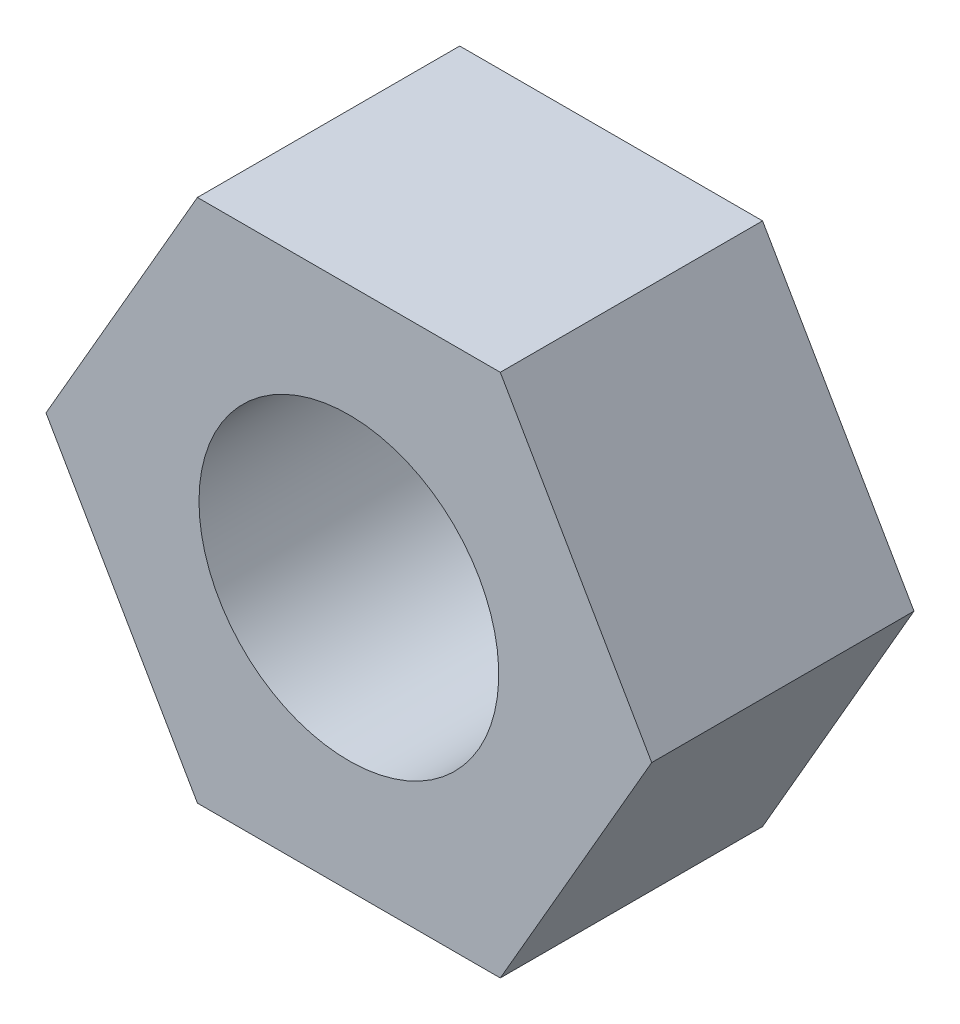
SolidWorks part; units mm, degrees
ref_plane "Front Plane" through (0, 0, 0) normal (0, 0, 1) x (1, 0, 0)
ref_plane "Top Plane" through (0, 0, 0) normal (0, 1, 0) x (1, 0, 0)
ref_plane "Right Plane" through (0, 0, 0) normal (1, 0, 0) x (0, 0, -1)
ref_plane "Plane1" through (0, 0, 177.8) normal (0, 0, 1) x (1, 0, 0)
sketch "Sketch1" plane through (0, 0, 177.8) normal (0, 0, 1) x (1, 0, 0)
  line L0 (-102.6529, -177.8) -> (102.6529, -177.8)
  line L1 (102.6529, -177.8) -> (205.3058, 0)
  line L2 (205.3058, 0) -> (102.6529, 177.8)
  line L3 (102.6529, 177.8) -> (-102.6529, 177.8)
  line L4 (-102.6529, 177.8) -> (-205.3058, 0)
  line L5 (-205.3058, 0) -> (-102.6529, -177.8)
  circle A0 centre (0, 0) radius 101.6
extrude "Boss-Extrude1" add sketch "Sketch1" against normal blind 177.8
